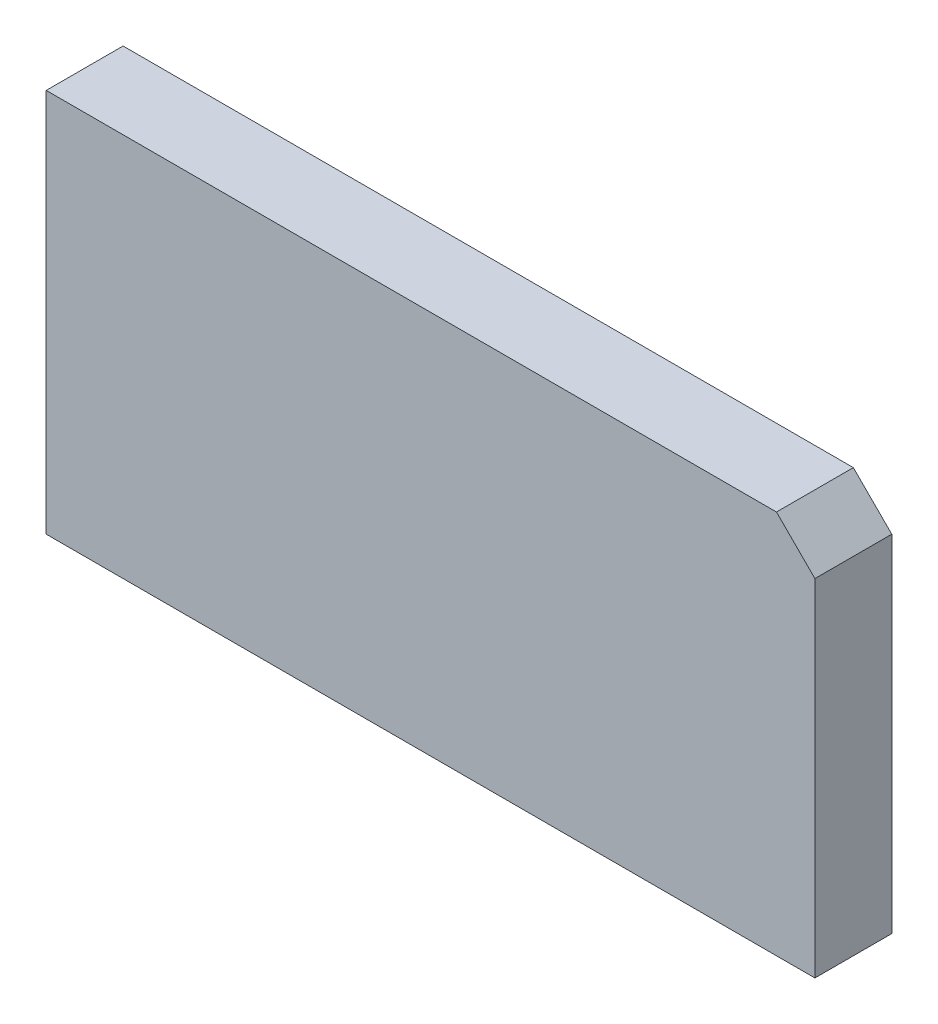
SolidWorks part; units mm, degrees
ref_plane "Front Plane" through (0, 0, 0) normal (0, 0, 1) x (1, 0, 0)
ref_plane "Top Plane" through (0, 0, 0) normal (0, 1, 0) x (1, 0, 0)
ref_plane "Right Plane" through (0, 0, 0) normal (1, 0, 0) x (0, 0, -1)
sketch "Sketch1" plane through (0, 0, 0) normal (0, 0, 1) x (1, 0, 0)
  line L1 (-1000, 500) -> (1000, 500)
  line L2 (-1000, 500) -> (-1000, -500)
  line L3 (-1000, -500) -> (1000, -500)
  line L4 (1000, 500) -> (1000, -500)
  dimension "table_width" = 1000
  dimension "table_length" = 2000
  dimension "D1" = 1000
  dimension "D2" = 500
extrude "Boss-Extrude1" add sketch "Sketch1" against normal blind 200
sketch "Sketch2" plane through (0, 0, 0) normal (0, 0, 1) x (1, 0, 0)
  line L0 (900, 500) -> (1000, 400)
  line L1 (1000, 500) -> (-1000, 500) construction
  line L2 (1000, -500) -> (1000, 500) construction
  line L3 (1000, 400) -> (1000, 500)
  line L4 (1000, 500) -> (900, 500)
  dimension "D1" = 45
  dimension "D2" = 100
extrude "Cut-Extrude1" cut sketch "Sketch2" against normal blind 200
equation "\"D1@Sketch1\"=\"table_length@Sketch1\"/2"
equation "\"D2@Sketch1\"=\"table_width@Sketch1\"/2"
